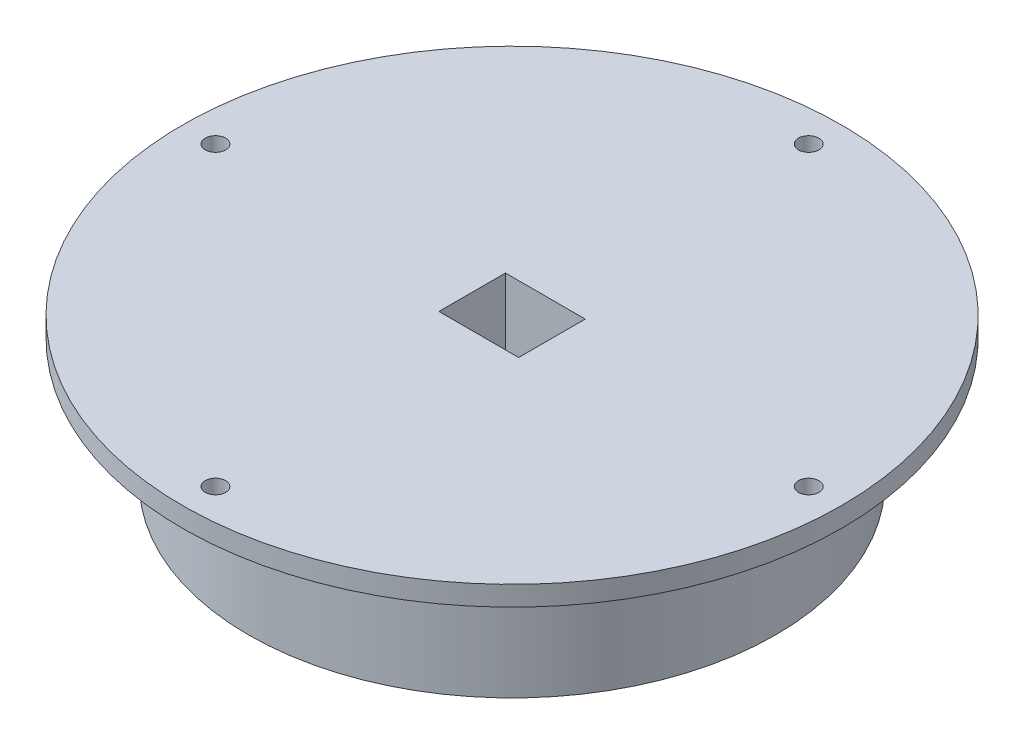
SolidWorks part; units mm, degrees
ref_plane "Plan de face" through (0, 0, 0) normal (0, 0, 1) x (1, 0, 0)
ref_plane "Plan de dessus" through (0, 0, 0) normal (0, 1, 0) x (1, 0, 0)
ref_plane "Plan de droite" through (0, 0, 0) normal (1, 0, 0) x (0, 0, -1)
sketch "Esquisse1" plane through (0, 0, 0) normal (0, 0, 1) x (1, 0, 0)
  line L14 (0, 0) -> (40, 0)
  line L15 (0, 0) -> (0, 22)
  line L16 (0, 22) -> (40, 22)
  line L17 (40, 0) -> (40, 19)
  line L19 (40, 22) -> (50, 22)
  line L21 (40, 19) -> (50, 19)
  line L22 (50, 22) -> (50, 19)
  dimension "D1" = 40
  dimension "D2" = 22
  dimension "D3" = 10
  dimension "D4" = 3
revolve "Révolution1" add sketch "Esquisse1" angle 360 about L15
sketch "Esquisse2" plane through (0, 22, 0) normal (0, 1, 0) x (1, 0, 0)
  line L1 (-6.05, 5.05) -> (6.05, 5.05)
  line L2 (-6.05, 5.05) -> (-6.05, -5.05)
  line L3 (-6.05, -5.05) -> (6.05, -5.05)
  line L4 (6.05, 5.05) -> (6.05, -5.05)
  dimension "D4" = 6.05
  dimension "D1" = 12.1
  dimension "D2" = 10.1
  dimension "D3" = 5.05
extrude "Enlèv. mat.-Extru.1" cut sketch "Esquisse2" against normal blind 21.3
sketch "Esquisse3" plane through (0, 22, 0) normal (0, 1, 0) x (1, 0, 0)
  circle A2 centre (45, 0) radius 1.55
  circle A3 centre (-45, 0) radius 1.55
  circle A4 centre (0, 45) radius 1.55
  circle A5 centre (0, -45) radius 1.55
  dimension "D1" = 3.1
extrude "Enlèv. mat.-Extru.2" cut sketch "Esquisse3" against normal blind 21.3
sketch "Esquisse5" plane through (0, 0.7, 0) normal (0, 1, 0) x (1, 0, 0)
  circle A0 centre (0, 0) radius 4.25
  dimension "D1" = 8.5
extrude "Enlèv. mat.-Extru.3" cut sketch "Esquisse5" against normal blind 21.3
